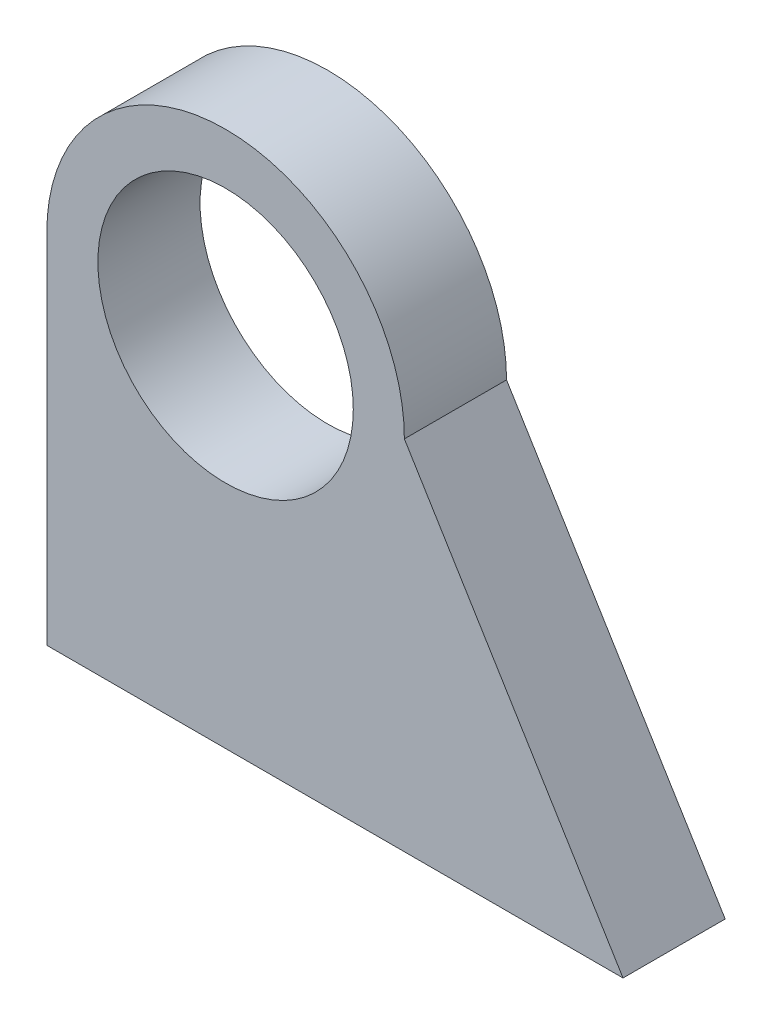
SolidWorks part; units mm, degrees
ref_plane "Front Plane" through (0, 0, 0) normal (0, 0, 1) x (1, 0, 0)
ref_plane "Top Plane" through (0, 0, 0) normal (0, 1, 0) x (1, 0, 0)
ref_plane "Right Plane" through (0, 0, 0) normal (1, 0, 0) x (0, 0, -1)
sketch "Sketch1" plane through (0, 0, 0) normal (0, 0, 1) x (1, 0, 0)
  line L0 (0, 35) -> (0, 0)
  line L1 (0, 0) -> (56.4024, 0)
  line L2 (56.4024, 0) -> (35, 35)
  arc A1 (0, 35) -> (35, 35) centre (17.5, 35) cw
  circle A2 centre (17.5, 35) radius 12.5
  circle A3 centre (35.9756, 11.2805) radius 10 construction
  point P5 (-39.6341, 31.7073)
  point P6 (23.3232, -1.8293)
  point P10 (14.4817, -4.878)
  point P11 (-17.5305, 6.5549)
  point P12 (0, 0)
  point P14 (37.5, 12.5)
  point P15 (56.4024, 0)
  point P16 (37.3476, 12.8049)
  point P17 (38.2622, 12.0427)
  dimension "D1" = 25
  dimension "D2" = 5
  dimension "D3" = 20
  dimension "D4" = 35
extrude "Boss-Extrude1" add sketch "Sketch1" along normal blind 10
